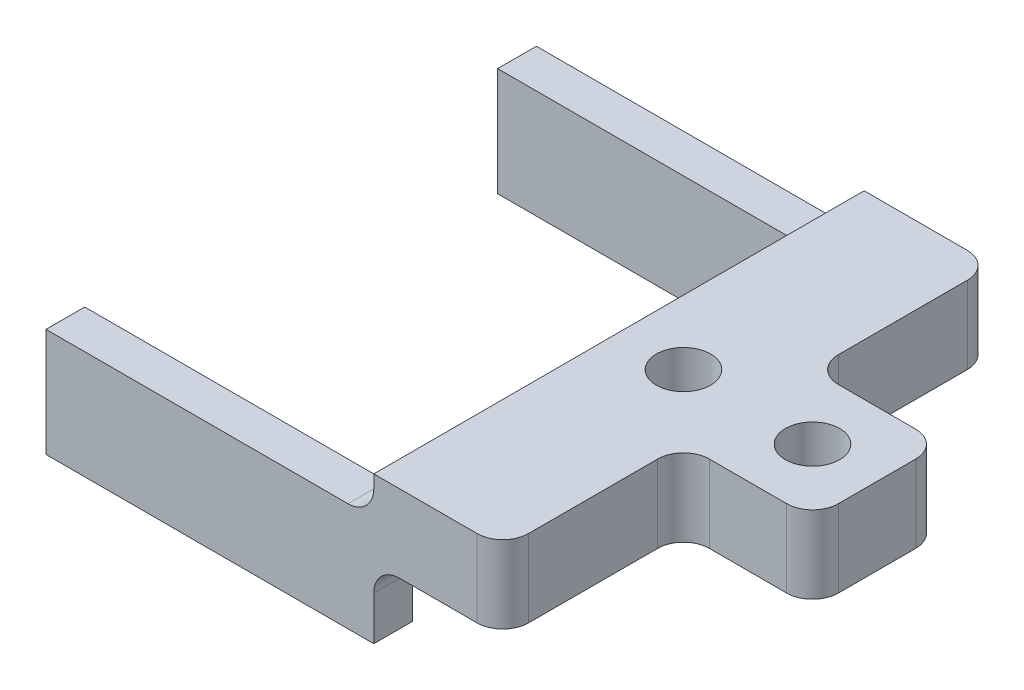
SolidWorks part; units mm, degrees
ref_plane "前视基准面" through (0, 0, 0) normal (0, 0, 1) x (1, 0, 0)
ref_plane "上视基准面" through (0, 0, 0) normal (0, 1, 0) x (1, 0, 0)
ref_plane "右视基准面" through (0, 0, 0) normal (1, 0, 0) x (0, 0, -1)
sketch "草图1" plane through (0, 0, 0) normal (0, 1, 0) x (1, 0, 0)
  line L1 (-76.2217, 79.6845) -> (-50.8217, 79.6845)
  line L2 (-76.2217, 79.6845) -> (-76.2217, 76.6845)
  line L3 (-76.2217, 76.6845) -> (-50.8217, 76.6845)
  line L4 (-50.8217, 79.6845) -> (-50.8217, 76.6845)
  line L5 (-76.2217, 44.6845) -> (-50.8217, 44.6845)
  line L6 (-76.2217, 44.6845) -> (-76.2217, 41.6845)
  line L7 (-76.2217, 41.6845) -> (-50.8217, 41.6845)
  line L8 (-50.8217, 44.6845) -> (-50.8217, 41.6845)
  dimension "D1" = 3
  dimension "D2" = 3
  dimension "D3" = 25.4
  dimension "D4" = 32
extrude "凸台-拉伸1" add sketch "草图1" along normal blind 8.4
sketch "草图2" plane through (0, 8.4, 0) normal (0, 1, 0) x (1, 0, 0)
  line L0 (-40.8217, 55.6845) -> (-40.8217, 41.6845)
  line L1 (-50.8217, 79.6845) -> (-40.8217, 79.6845)
  line L2 (-50.8217, 79.6845) -> (-50.8217, 41.6845)
  line L3 (-50.8217, 41.6845) -> (-40.8217, 41.6845)
  line L4 (-40.8217, 79.6845) -> (-40.8217, 65.6845)
  line L5 (-40.8217, 65.6845) -> (-30.8217, 65.6845)
  line L7 (-40.8217, 55.6845) -> (-30.8217, 55.6845)
  line L8 (-30.8217, 65.6845) -> (-30.8217, 55.6845)
  point P9 (-30.8217, 60.6845)
  point P10 (-50.8217, 60.6845)
  dimension "D1" = 10
  dimension "D2" = 38
  dimension "D3" = 10
  dimension "D4" = 0
extrude "凸台-拉伸2" add sketch "草图2" along normal blind 3 and the other way blind 3
fillet "圆角1" radius 2 10 edges at (-30.8217, 8.4, -65.6845) (-30.8217, 8.4, -55.6845) (-40.8217, 8.4, -41.6845) (-40.8217, 8.4, -55.6845) (-40.8217, 8.4, -65.6845) (-40.8217, 8.4, -79.6845) (-50.8217, 5.4, -78.1845) (-50.8217, 5.4, -43.1845) (-50.8217, 8.4, -43.1845) (-50.8217, 8.4, -78.1845)
sketch "草图3" plane through (0, 11.4, 0) normal (0, 1, 0) x (1, 0, 0)
  line L0 (-50.8217, 79.6845) -> (-50.8217, 41.6845) construction
  line L1 (-30.8217, 57.6845) -> (-30.8217, 63.6845) construction
  circle A0 centre (-45.8217, 60.6845) radius 2.1
  circle A1 centre (-35.8217, 60.6845) radius 2.1
  point P6 (-50.8217, 60.6845)
  dimension "D1" = 4.2
  dimension "D2" = 4.2
  dimension "D3" = 10
  dimension "D4" = 0
  dimension "D5" = 0
  dimension "D6" = 5
extrude "切除-拉伸1" cut sketch "草图3" along direction (0, 1, 0) on the side against the normal up to next (6 mm away)
